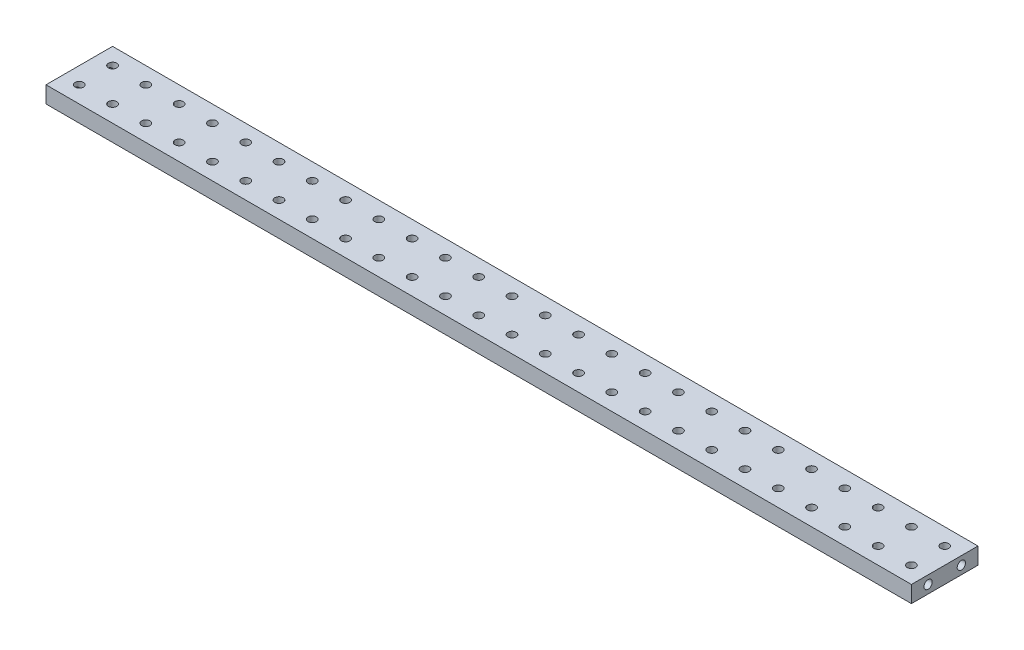
SolidWorks part; units mm, degrees
ref_plane "Front Plane" through (0, 0, 0) normal (0, 0, 1) x (1, 0, 0)
ref_plane "Top Plane" through (0, 0, 0) normal (0, 1, 0) x (1, 0, 0)
ref_plane "Right Plane" through (0, 0, 0) normal (1, 0, 0) x (0, 0, -1)
sketch "Sketch1" plane through (0, 0, 0) normal (0, 1, 0) x (1, 0, 0)
  line L1 (-330.2, -25.4) -> (330.2, -25.4)
  line L2 (-330.2, -25.4) -> (-330.2, 25.4)
  line L3 (-330.2, 25.4) -> (330.2, 25.4)
  line L4 (330.2, -25.4) -> (330.2, 25.4)
  line L5 (0, 25.4) -> (0, -25.4) construction
  line L6 (-330.2, 0) -> (330.2, 0) construction
  point P0 (0, 0)
  dimension "D1" = 50.8
  dimension "D2" = 660.4
extrude "Boss-Extrude1" add sketch "Sketch1" along normal blind 12.7
sketch "Sketch2" plane through (-330.2, 0, 0) normal (-1, 0, 0) x (0, 0, 1)
  line L0 (-25.4, 12.7) -> (-25.4, 0) construction
  circle A0 centre (-12.7, 6.35) radius 3.175
  circle A1 centre (12.7, 6.35) radius 3.175
  point P4 (-25.4, 6.35)
  dimension "D1" = 6.35
  dimension "D2" = 12.7
  dimension "D3" = 2
extrude "Cut-Extrude1" cut sketch "Sketch2" against normal blind 12.7
sketch "Sketch3" plane through (330.2, 0, 0) normal (1, 0, 0) x (0, 0, -1)
  line L1 (-25.4, 12.7) -> (-25.4, 0) construction
  circle A0 centre (-12.7, 6.35) radius 3.175
  circle A1 centre (12.7, 6.35) radius 3.175
  point P5 (-25.4, 6.35)
  dimension "D1" = 6.35
  dimension "D2" = 12.7
  dimension "D3" = 2
extrude "Cut-Extrude2" cut sketch "Sketch3" against normal blind 12.7
sketch "Sketch4" plane through (0, 12.7, 0) normal (0, 1, 0) x (1, 0, 0)
  line L0 (330.2, 25.4) -> (-330.2, 25.4) construction
  line L1 (-330.2, 25.4) -> (-330.2, -25.4) construction
  circle A0 centre (-317.5, 12.7) radius 3.175
  circle A1 centre (-292.1, 12.7) radius 3.175
  circle A2 centre (-266.7, 12.7) radius 3.175
  circle A3 centre (-241.3, 12.7) radius 3.175
  circle A4 centre (-215.9, 12.7) radius 3.175
  circle A5 centre (-190.5, 12.7) radius 3.175
  circle A6 centre (-165.1, 12.7) radius 3.175
  circle A7 centre (-139.7, 12.7) radius 3.175
  circle A8 centre (-114.3, 12.7) radius 3.175
  circle A9 centre (-88.9, 12.7) radius 3.175
  circle A10 centre (-63.5, 12.7) radius 3.175
  circle A11 centre (-38.1, 12.7) radius 3.175
  circle A12 centre (-12.7, 12.7) radius 3.175
  circle A13 centre (12.7, 12.7) radius 3.175
  circle A14 centre (38.1, 12.7) radius 3.175
  circle A15 centre (63.5, 12.7) radius 3.175
  circle A16 centre (88.9, 12.7) radius 3.175
  circle A17 centre (114.3, 12.7) radius 3.175
  circle A18 centre (139.7, 12.7) radius 3.175
  circle A19 centre (165.1, 12.7) radius 3.175
  circle A20 centre (190.5, 12.7) radius 3.175
  circle A21 centre (215.9, 12.7) radius 3.175
  circle A22 centre (241.3, 12.7) radius 3.175
  circle A23 centre (266.7, 12.7) radius 3.175
  circle A24 centre (-292.1, -12.7) radius 3.175
  circle A25 centre (-266.7, -12.7) radius 3.175
  circle A26 centre (-241.3, -12.7) radius 3.175
  circle A27 centre (-215.9, -12.7) radius 3.175
  circle A28 centre (-190.5, -12.7) radius 3.175
  circle A29 centre (-165.1, -12.7) radius 3.175
  circle A30 centre (-139.7, -12.7) radius 3.175
  circle A31 centre (-114.3, -12.7) radius 3.175
  circle A32 centre (-88.9, -12.7) radius 3.175
  circle A33 centre (-63.5, -12.7) radius 3.175
  circle A34 centre (-38.1, -12.7) radius 3.175
  circle A35 centre (-12.7, -12.7) radius 3.175
  circle A36 centre (12.7, -12.7) radius 3.175
  circle A37 centre (38.1, -12.7) radius 3.175
  circle A38 centre (63.5, -12.7) radius 3.175
  circle A39 centre (88.9, -12.7) radius 3.175
  circle A40 centre (114.3, -12.7) radius 3.175
  circle A41 centre (139.7, -12.7) radius 3.175
  circle A42 centre (165.1, -12.7) radius 3.175
  circle A43 centre (190.5, -12.7) radius 3.175
  circle A44 centre (215.9, -12.7) radius 3.175
  circle A45 centre (241.3, -12.7) radius 3.175
  circle A46 centre (266.7, -12.7) radius 3.175
  circle A47 centre (-317.5, -12.7) radius 3.175
  circle A48 centre (292.1, 12.7) radius 3.175
  circle A49 centre (317.5, 12.7) radius 3.175
  circle A50 centre (342.9, 12.7) radius 3.175
  circle A51 centre (368.3, 12.7) radius 3.175
  circle A52 centre (393.7, 12.7) radius 3.175
  circle A53 centre (419.1, 12.7) radius 3.175
  circle A54 centre (444.5, 12.7) radius 3.175
  circle A55 centre (469.9, 12.7) radius 3.175
  circle A56 centre (495.3, 12.7) radius 3.175
  circle A57 centre (520.7, 12.7) radius 3.175
  circle A58 centre (546.1, 12.7) radius 3.175
  circle A59 centre (571.5, 12.7) radius 3.175
  circle A60 centre (596.9, 12.7) radius 3.175
  circle A61 centre (622.3, 12.7) radius 3.175
  circle A62 centre (647.7, 12.7) radius 3.175
  circle A63 centre (673.1, 12.7) radius 3.175
  circle A64 centre (698.5, 12.7) radius 3.175
  circle A65 centre (723.9, 12.7) radius 3.175
  circle A66 centre (749.3, 12.7) radius 3.175
  circle A67 centre (774.7, 12.7) radius 3.175
  circle A68 centre (800.1, 12.7) radius 3.175
  circle A69 centre (825.5, 12.7) radius 3.175
  circle A70 centre (850.9, 12.7) radius 3.175
  circle A71 centre (876.3, 12.7) radius 3.175
  circle A72 centre (292.1, -12.7) radius 3.175
  circle A73 centre (317.5, -12.7) radius 3.175
  circle A74 centre (342.9, -12.7) radius 3.175
  circle A75 centre (368.3, -12.7) radius 3.175
  circle A76 centre (393.7, -12.7) radius 3.175
  circle A77 centre (419.1, -12.7) radius 3.175
  circle A78 centre (444.5, -12.7) radius 3.175
  circle A79 centre (469.9, -12.7) radius 3.175
  circle A80 centre (495.3, -12.7) radius 3.175
  circle A81 centre (520.7, -12.7) radius 3.175
  circle A82 centre (546.1, -12.7) radius 3.175
  circle A83 centre (571.5, -12.7) radius 3.175
  circle A84 centre (596.9, -12.7) radius 3.175
  circle A85 centre (622.3, -12.7) radius 3.175
  circle A86 centre (647.7, -12.7) radius 3.175
  circle A87 centre (673.1, -12.7) radius 3.175
  circle A88 centre (698.5, -12.7) radius 3.175
  circle A89 centre (723.9, -12.7) radius 3.175
  circle A90 centre (749.3, -12.7) radius 3.175
  circle A91 centre (774.7, -12.7) radius 3.175
  circle A92 centre (800.1, -12.7) radius 3.175
  circle A93 centre (825.5, -12.7) radius 3.175
  circle A94 centre (850.9, -12.7) radius 3.175
  circle A95 centre (876.3, -12.7) radius 3.175
  dimension "D1" = 6.35
  dimension "D2" = 12.7
  dimension "D3" = 12.7
  dimension "D4" = 48
  dimension "D5" = 2
extrude "Cut-Extrude3" cut sketch "Sketch4" against normal through all
